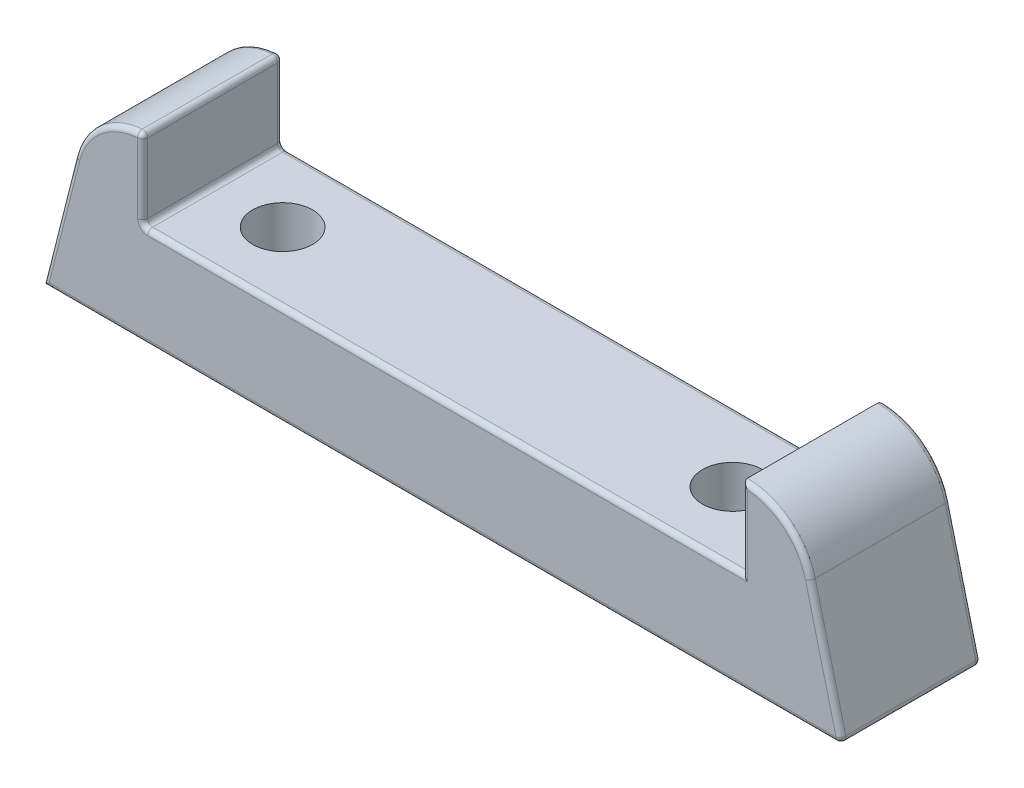
SolidWorks part; units mm, degrees
ref_plane "Front Plane" through (0, 0, 0) normal (0, 0, 1) x (1, 0, 0)
ref_plane "Top Plane" through (0, 0, 0) normal (0, 1, 0) x (1, 0, 0)
ref_plane "Right Plane" through (0, 0, 0) normal (1, 0, 0) x (0, 0, -1)
sketch "Sketch1" plane through (0, 0, 0) normal (0, 0, 1) x (1, 0, 0)
  line L0 (-40, 0) -> (40, 0)
  line L2 (30, 10) -> (-30, 10)
  line L3 (-30, 10) -> (-30, 18)
  line L4 (-36.7866, 12.7151) -> (-40, 0)
  line L5 (0, 0) -> (0, -21.3097) construction
  line L6 (36.7866, 12.7151) -> (40, 0)
  line L7 (30, 10) -> (30, 18)
  arc A0 (-30, 18) -> (-36.7866, 12.7151) centre (-30, 11) ccw
  arc A1 (30, 18) -> (36.7866, 12.7151) centre (30, 11) cw
  dimension "D4" = 7
  dimension "D1" = 40
  dimension "D2" = 30
  dimension "D3" = 10
  dimension "D5" = 8
extrude "Boss-Extrude1" add sketch "Sketch1" along normal mid plane 14
sketch "Sketch2" plane through (0, 10, 0) normal (0, 1, 0) x (1, 0, 0)
  line L0 (0, -7) -> (0, 7) construction
  line L1 (30, 7) -> (-30, 7) construction
  circle A0 centre (-23, 0) radius 3
  circle A2 centre (22, 0) radius 3
  point P9 (0, 0)
  dimension "D1" = 6
  dimension "D5" = 6
  dimension "D2" = 23
  dimension "D3" = 22
  dimension "D4" = 7
extrude "Cut-Extrude1" cut sketch "Sketch2" against normal blind 14
fillet "Fillet1" radius 0.5 19 edges at (0, 0, -7) (34.3008, 16.5229, -7) (30, 14, -7) (0, 10, -7) (-34.3008, 16.5229, -7) (-38.3933, 6.3576, -7) (40, 0, 0) (38.3933, 6.3576, -7) (-34.3008, 16.5229, 7) (0, 10, 7) (30, 14, 7) (34.3008, 16.5229, 7) (38.3933, 6.3576, 7) (0, 0, 7) (-38.3933, 6.3576, 7) (-30, 10, 0) (-30, 14, 7) (-30, 18, 0) (-30, 14, -7)
